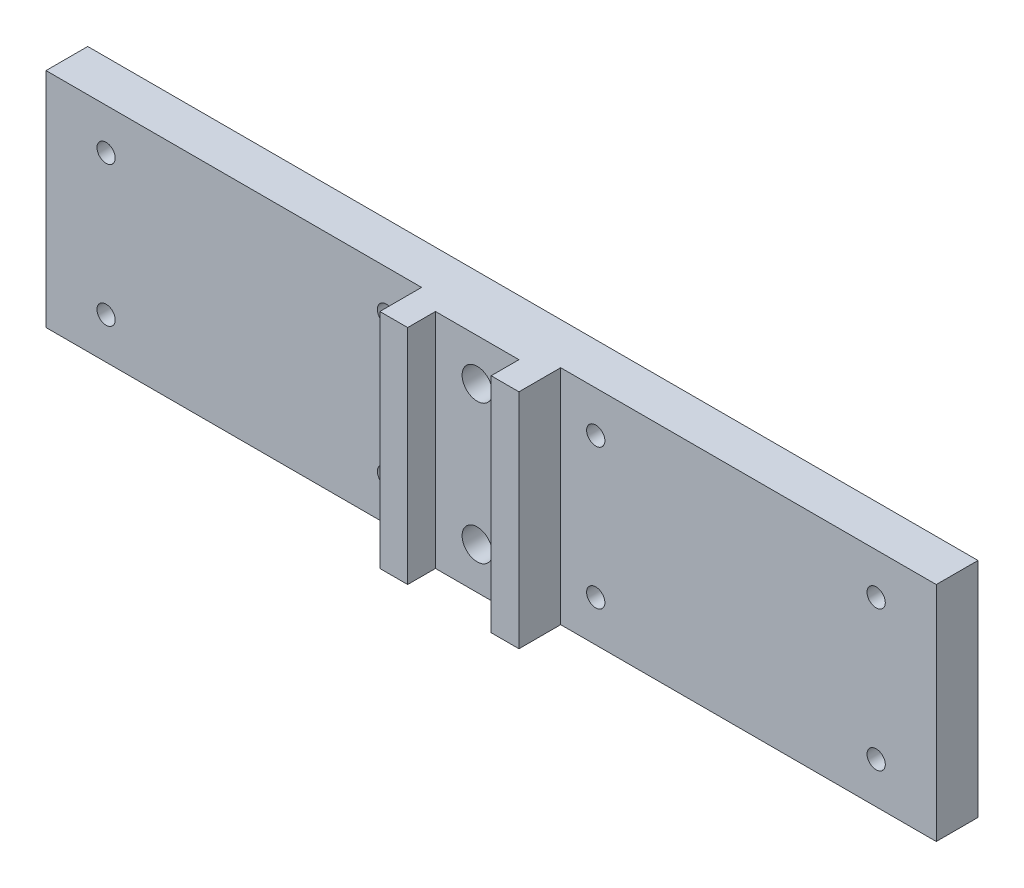
SolidWorks part; units mm, degrees
ref_plane "Front Plane" through (0, 0, 0) normal (0, 0, 1) x (1, 0, 0)
ref_plane "Top Plane" through (0, 0, 0) normal (0, 1, 0) x (1, 0, 0)
ref_plane "Right Plane" through (0, 0, 0) normal (1, 0, 0) x (0, 0, -1)
sketch "Sketch1" plane through (0, 0, 0) normal (0, 0, 1) x (1, 0, 0)
  line L1 (0, 0) -> (101.6, 0)
  line L2 (0, 0) -> (0, 25.4)
  line L3 (0, 25.4) -> (101.6, 25.4)
  line L4 (101.6, 0) -> (101.6, 25.4)
  dimension "D1" = 25.4
  dimension "D2" = 101.6
extrude "Boss-Extrude1" add sketch "Sketch1" along normal blind 9.525
sketch "Sketch2" plane through (0, 25.4, 0) normal (0, 1, 0) x (1, 0, 0)
  line L0 (50.8, 0) -> (50.8, -9.525) construction
  line L1 (101.6, 0) -> (0, 0) construction
  line L2 (101.6, -9.525) -> (0, -9.525) construction
  line L3 (55.5625, -9.525) -> (55.5625, -6.35)
  line L4 (0, -9.525) -> (42.8625, -9.525)
  line L5 (0, -9.525) -> (0, -4.7625)
  line L6 (0, -4.7625) -> (42.8625, -4.7625)
  line L7 (42.8625, -9.525) -> (42.8625, -4.7625)
  line L8 (55.5625, -9.525) -> (46.0375, -9.525)
  line L10 (55.5625, -6.35) -> (46.0375, -6.35)
  line L11 (46.0375, -9.525) -> (46.0375, -6.35)
  line L12 (58.7375, -9.525) -> (58.7375, -4.7625)
  line L13 (101.6, -4.7625) -> (58.7375, -4.7625)
  line L14 (101.6, -9.525) -> (101.6, -4.7625)
  line L15 (101.6, -9.525) -> (58.7375, -9.525)
  dimension "D1" = 4.7625
  dimension "D2" = 6.35
  dimension "D3" = 9.525
  dimension "D4" = 3.175
extrude "Cut-Extrude1" cut sketch "Sketch2" against normal through all
hole_wizard "#8-32 Tapped Hole1" positions "Sketch7" profile "Sketch8" tap size "#8-32" standard "ANSI Inch" end condition through all
sketch "Sketch7" plane through (0, 0, 6.35) normal (0, 0, 1) x (1, 0, 0)
  line L0 (55.5625, 12.7) -> (46.0375, 12.7) construction
  line L1 (55.5625, 0) -> (55.5625, 25.4) construction
  line L2 (46.0375, 0) -> (46.0375, 25.4) construction
  line L4 (50.8, 25.4) -> (50.8, 0) construction
  line L5 (55.5625, 25.4) -> (46.0375, 25.4) construction
  line L6 (55.5625, 0) -> (46.0375, 0) construction
  point P16 (50.8, 4.7625)
  point P19 (50.8, 20.6375)
  dimension "D1" = 7.9375
sketch "Sketch8" plane through (50.8, 4.7625, 6.35) normal (1, 0, 0) x (0, -1, 0)
  line L0 (0, 0) -> (0, 6.35)
  line L1 (0, 6.35) -> (1.7272, 6.35)
  line L2 (1.7272, 6.35) -> (1.7272, 0)
  line L5 (1.7272, 0) -> (0, 0)
  line L11 (0, -6.35) -> (0, 107.95) construction
  dimension "Thread Major Dia." = 3.4544
  dimension "Thru Tap Drill Depth" = 6.35
hole_wizard "#45 (0.082) Diameter Hole1" positions "Sketch14" profile "Sketch13" hole size "#45" standard "ANSI Inch"
sketch "Sketch14" plane through (0, 0, 0) normal (0, 0, -1) x (-1, 0, 0)
  line L0 (-50.8, 25.4) -> (-50.8, 0) construction
  line L1 (-101.6, 25.4) -> (0, 25.4) construction
  line L2 (0, 0) -> (-101.6, 0) construction
  line L4 (-50.8, 12.7) -> (0, 12.7) construction
  line L5 (0, 25.4) -> (0, 0) construction
  line L9 (-38.86, 20.7) -> (-6.86, 20.7) construction
  line L11 (-22.86, 20.7) -> (-22.86, 12.7) construction
  line L12 (-38.86, 4.7) -> (-6.86, 4.7) construction
  line L13 (-62.74, 4.7) -> (-94.74, 4.7) construction
  line L14 (-62.74, 20.7) -> (-94.74, 20.7) construction
  point P19 (-38.86, 20.7)
  point P20 (-6.86, 20.7)
  point P28 (-38.86, 4.7)
  point P29 (-6.86, 4.7)
  point P30 (-62.74, 4.7)
  point P31 (-94.74, 4.7)
  point P32 (-62.74, 20.7)
  point P33 (-94.74, 20.7)
  dimension "D1" = 32
  dimension "D2" = 8
  dimension "D3" = 27.94
sketch "Sketch13" plane through (38.86, 20.7, 0) normal (1, 0, 0) x (0, 1, 0)
  line L0 (0, 0) -> (0, 10.2777)
  line L1 (0, 10.2777) -> (1.0414, 9.652)
  line L2 (1.0414, 9.652) -> (1.0414, 0)
  line L5 (1.0414, 0) -> (0, 0)
  line L10 (0, 10.2777) -> (-1.0414, 9.652) construction
  line L11 (0, -6.35) -> (0, 107.95) construction
  dimension "Hole Dia." = 2.0828
  dimension "Hole Depth" = 9.652
  dimension "Drill Angle" = 118
